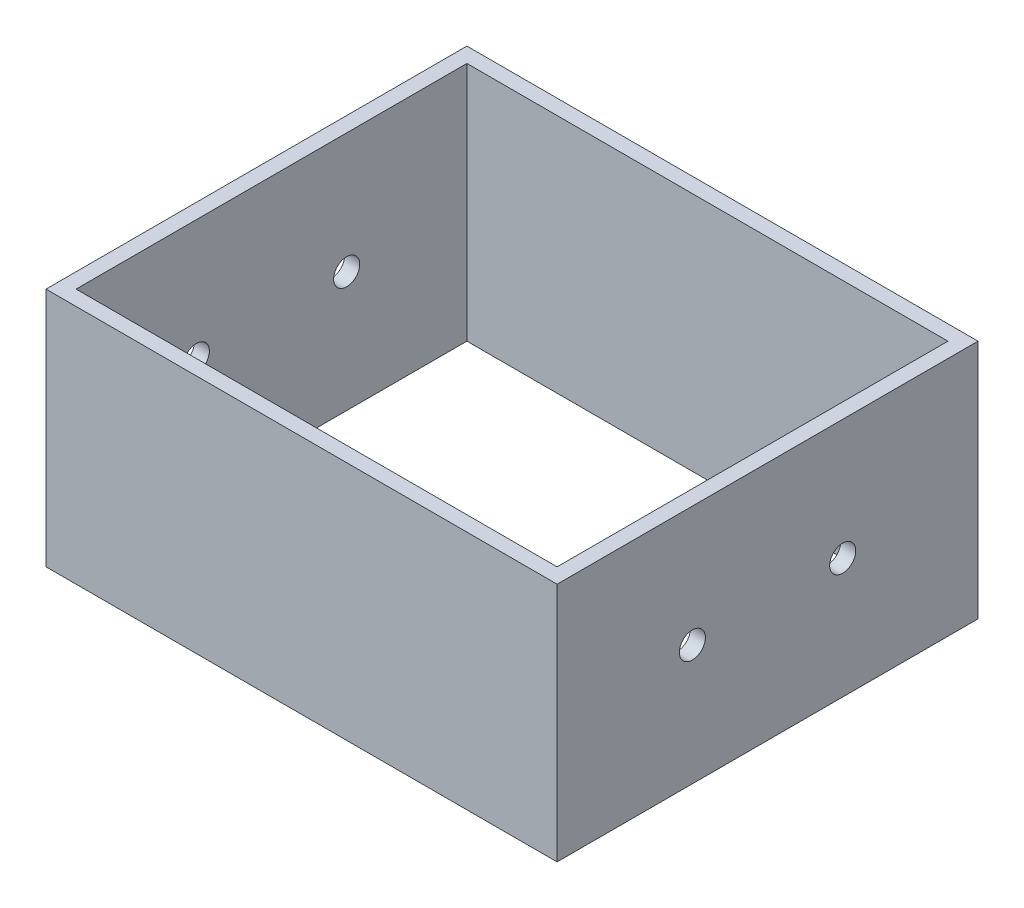
SolidWorks part; units mm, degrees
material "ABS"
ref_plane "Front Plane" through (0, 0, 0) normal (0, 0, 1) x (1, 0, 0)
ref_plane "Top Plane" through (0, 0, 0) normal (0, 1, 0) x (1, 0, 0)
ref_plane "Right Plane" through (0, 0, 0) normal (1, 0, 0) x (0, 0, -1)
sketch "Sketch1" plane through (0, 0, 0) normal (0, 1, 0) x (1, 0, 0)
  line L0 (-6.35, -6.35) -> (209.55, -6.35)
  line L1 (0, 0) -> (203.2, 0)
  line L2 (0, 0) -> (0, 165.1)
  line L3 (0, 165.1) -> (203.2, 165.1)
  line L4 (203.2, 0) -> (203.2, 165.1)
  line L5 (209.55, -6.35) -> (209.55, 171.45)
  line L6 (-6.35, 171.45) -> (209.55, 171.45)
  line L7 (-6.35, -6.35) -> (-6.35, 171.45)
  dimension "D1" = 165.1
  dimension "D2" = 203.2
  dimension "D3" = 6.35
extrude "Boss-Extrude1" add sketch "Sketch1" along normal blind 101.6
sketch "Sketch2" plane through (209.55, 0, 0) normal (1, 0, 0) x (0, 0, -1)
  line L0 (-6.35, 101.6) -> (-6.35, 0) construction
  line L1 (171.45, 101.6) -> (171.45, 0) construction
  circle A0 centre (50.8, 50.8) radius 5.4993
  circle A1 centre (114.3, 50.8) radius 5.4993
  point P8 (-6.35, 50.8)
  dimension "D1" = 57.15
  dimension "D3" = 10.9985
  dimension "D2" = 57.15
extrude "Cut-Extrude1" cut sketch "Sketch2" against normal through all
